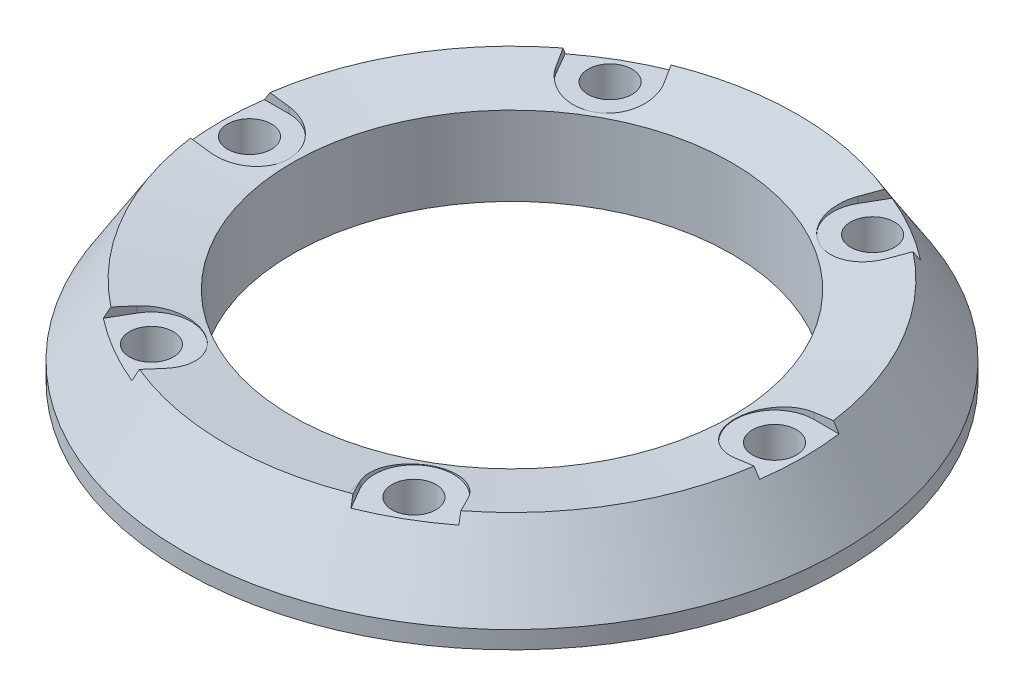
SolidWorks part; units mm, degrees
material "Acrylic (Medium-high impact)"
ref_plane "Front" through (0, 0, 0) normal (0, 0, 1) x (1, 0, 0)
ref_plane "Top" through (0, 0, 0) normal (0, 1, 0) x (1, 0, 0)
ref_plane "Right" through (0, 0, 0) normal (1, 0, 0) x (0, 0, -1)
sketch "Sketch6" plane through (0, 0, 0) normal (0, 0, 1) x (1, 0, 0)
  line L0 (12.5, 0) -> (18.75, 0)
  line L1 (18.75, 0) -> (18.75, 1)
  line L2 (18.75, 1) -> (16.25, 5)
  line L3 (16.25, 5) -> (12.5, 4.5)
  line L4 (12.5, 4.5) -> (12.5, 0)
  line L5 (0, 0) -> (0, 7.5401) construction
  dimension "D1" = 5
  dimension "D2" = 1
  dimension "D3" = 2.5
  dimension "D4" = 6.25
  dimension "D5" = 4.5
  dimension "D6" = 12.5
revolve "Revolve1" add sketch "Sketch6" angle 360 about L5
sketch "Sketch7" plane through (0, 0, 0) normal (0, -1, 0) x (1, 0, 0)
  circle A0 centre (14.9999, 0.0647) radius 1.25
  dimension "D2" = 2.5
  dimension "D1" = 15
extrude "Cut-Extrude2" cut sketch "Sketch7" against normal through all
ref_plane "Plane3" through (0, 5, 0) normal (0, 1, 0) x (-1, 0, 0)
sketch "Sketch8" plane through (0, 5, 0) normal (0, 1, 0) x (-1, 0, 0)
  line L0 (-14.9999, 2.3147) -> (-18.7086, 2.3147)
  line L1 (-18.7086, 2.3147) -> (-18.7086, -2.1853)
  line L2 (-18.7086, -2.1853) -> (-14.9999, -2.1853)
  arc A2 (-12.7499, 0.0647) -> (-12.7499, 0.0647) centre (-14.9999, 0.0647) ccw
  arc A3 (-14.9999, -2.1853) -> (-14.9999, 2.3147) centre (-14.9999, 0.0647) ccw
  dimension "D1" = 1
extrude "Cut-Extrude3" cut sketch "Sketch8" against normal blind 0.5
pattern_circular "CirPattern1" count 6 over 360 about axis through (0, 0, 0) along (0, 1, 0) of "Cut-Extrude2", "Cut-Extrude3"
